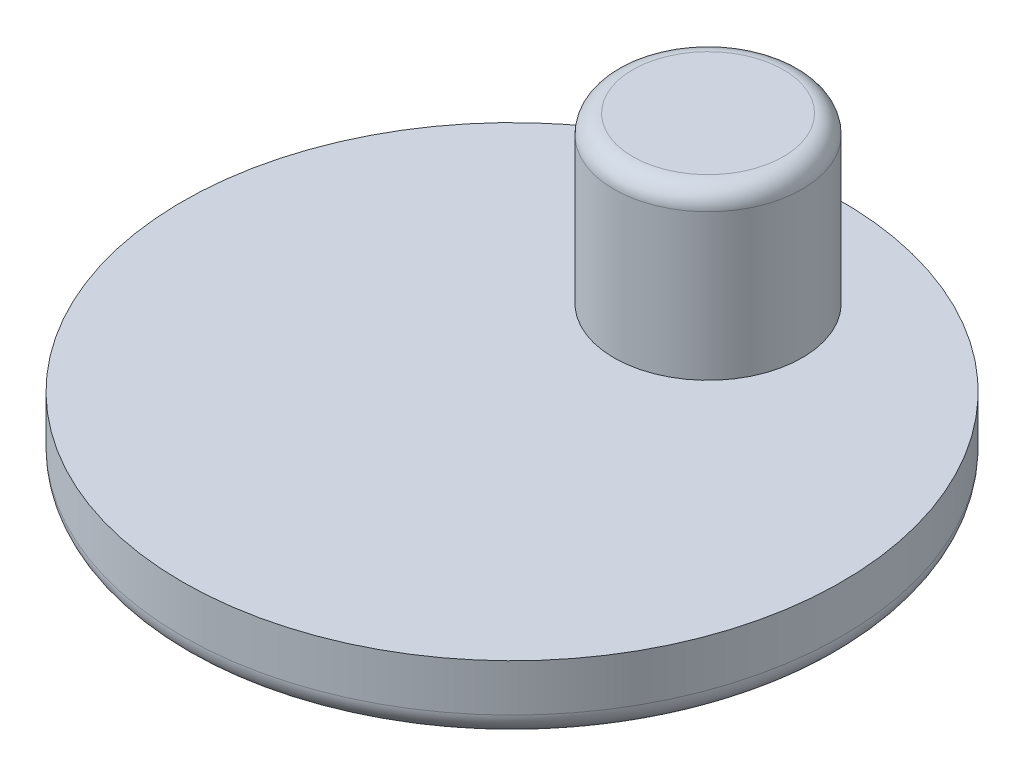
SolidWorks part; units mm, degrees
ref_plane "Front Plane" through (0, 0, 0) normal (0, 0, 1) x (1, 0, 0)
ref_plane "Top Plane" through (0, 0, 0) normal (0, 1, 0) x (1, 0, 0)
ref_plane "Right Plane" through (0, 0, 0) normal (1, 0, 0) x (0, 0, -1)
sketch "Sketch1" plane through (0, 0, 0) normal (0, 1, 0) x (1, 0, 0)
  line L0 (0, 7) -> (6.51, 7) construction
  circle A0 centre (0, 0) radius 7
  dimension "D1" = 14
extrude "Boss-Extrude1" add sketch "Sketch1" along normal blind 1.5
sketch "Sketch2" plane through (0, 1.5, -3.6335) normal (0, 1, 0) x (1, 0, 0)
  circle A0 centre (0.4585, 0.0707) radius 2
  circle A1 centre (0.4585, 0.0707) radius 2 construction
  dimension "D1" = 4
  dimension "D2" = 0
extrude "Boss-Extrude2" add sketch "Sketch2" along normal blind 3.5
fillet "Fillet1" radius 0.4 1 edges at (0.4585, 5, -1.7042)
fillet "Fillet2" radius 0.5 1 edges at (0, 0, 7)
